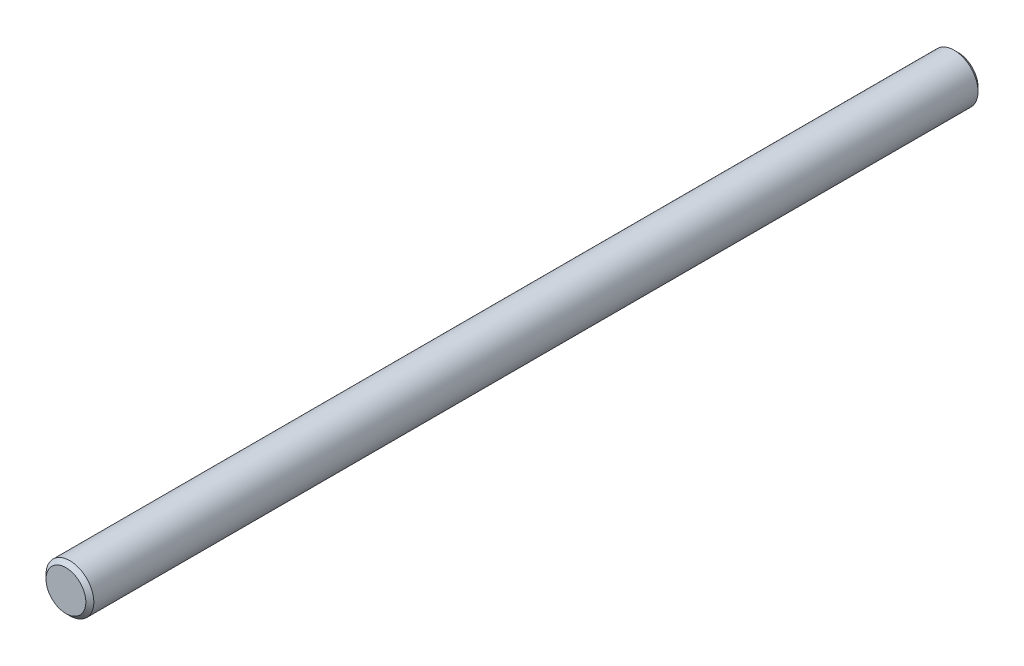
SolidWorks part; units mm, degrees
ref_plane "Plan de face" through (0, 0, 0) normal (0, 0, 1) x (1, 0, 0)
ref_plane "Plan de dessus" through (0, 0, 0) normal (0, 1, 0) x (1, 0, 0)
ref_plane "Plan de droite" through (0, 0, 0) normal (1, 0, 0) x (0, 0, -1)
ref_plane "Plan1" through (0, 0, 0) normal (0, -1, 0) x (1, 0, 0)
sketch "Esquisse1" plane through (0, 0, 0) normal (0, -1, 0) x (1, 0, 0)
  line L0 (1.25, 28) -> (0, 28)
  line L1 (0, 28) -> (0, -28)
  line L2 (0, -28) -> (1.25, -28)
  line L3 (1.25, -28) -> (1.5, -27.75)
  line L4 (1.5, -27.75) -> (1.5, 27.75)
  line L5 (1.5, 27.75) -> (1.25, 28)
  line L6 (0, 28) -> (0, -28) construction
  line L7 (0, 18.9373) -> (0, -18.5683) construction
  point P4 (1.5, -28)
  point P5 (1.5, 28)
  dimension "D1" = 56
  dimension "D2" = 3
revolve "Révolution1" add sketch "Esquisse1" angle 360 about L6
